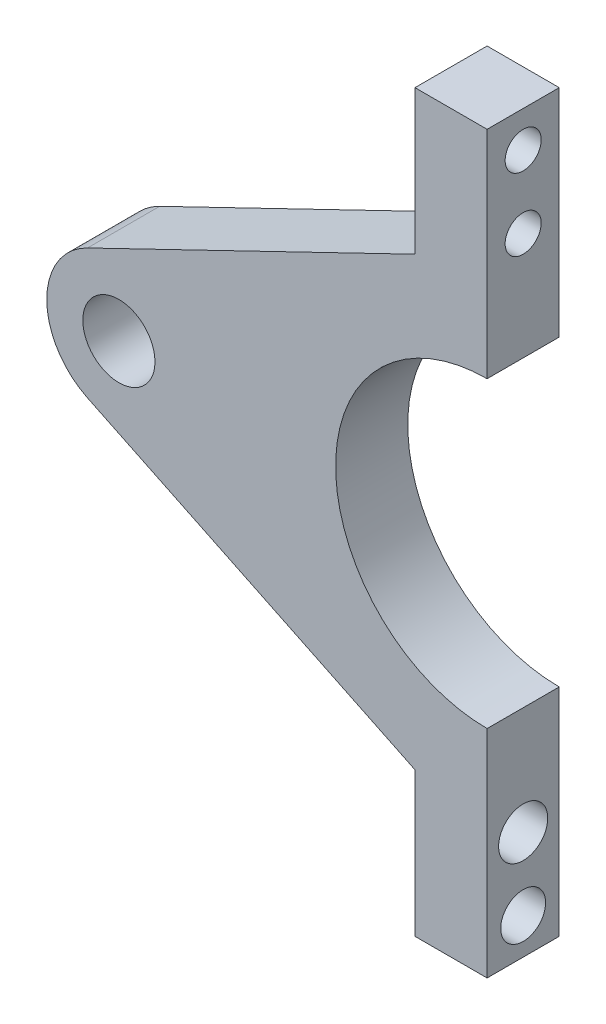
SolidWorks part; units mm, degrees
ref_plane "Front Plane" through (0, 0, 0) normal (0, 0, 1) x (1, 0, 0)
ref_plane "Top Plane" through (0, 0, 0) normal (0, 1, 0) x (1, 0, 0)
ref_plane "Right Plane" through (0, 0, 0) normal (1, 0, 0) x (0, 0, -1)
sketch "Sketch1" plane through (0, 0, 0) normal (0, 0, 1) x (1, 0, 0)
  line L0 (-122.0959, 24.2997) -> (-122.0959, 54.25)
  line L1 (-122.0959, 54.25) -> (-132.0959, 54.25)
  line L2 (-132.0959, 54.25) -> (-132.0959, 34.25)
  line L3 (-132.0959, 34.25) -> (-177.4962, 12.3029)
  line L4 (-24.0245, 3.2997) -> (-196.1204, 3.2997) construction
  line L5 (-122.0959, -17.7003) -> (-122.0959, -47.6506)
  line L6 (-122.0959, -47.6506) -> (-132.0959, -47.6506)
  line L7 (-132.0959, -47.6506) -> (-132.0959, -27.6506)
  line L8 (-132.0959, -27.6506) -> (-177.4962, -5.7035)
  arc A2 (-177.4962, 12.3029) -> (-177.4962, -5.7035) centre (-173.1439, 3.2997) ccw
  arc A3 (-122.0959, 24.2997) -> (-122.0959, -17.7003) centre (-122.0959, 3.2997) ccw
  point P2 (-183.1439, 3.2997)
  dimension "D2" = 101.9006
  dimension "D6" = 10
  dimension "D1" = 42
  dimension "D3" = 10
  dimension "D4" = 20
  dimension "D5" = 61.048
extrude "Boss-Extrude2" add sketch "Sketch1" against normal blind 10
sketch "Sketch2" plane through (0, 0, 0) normal (0, 0, 1) x (1, 0, 0)
  circle A0 centre (-173.1439, 3.2997) radius 5
  dimension "D1" = 10
extrude "Cut-Extrude1" cut sketch "Sketch2" against normal through all
sketch "Sketch3" plane through (-122.0959, 0, 0) normal (1, 0, 0) x (0, 0, -1)
  line L0 (10, 54.25) -> (0, 54.25) construction
  line L1 (10, -47.6506) -> (0, -47.6506) construction
  circle A0 centre (5, 49.25) radius 2.5
  circle A1 centre (5, 39.25) radius 2.5
  circle A2 centre (5, -42.6506) radius 3.1126
  circle A3 centre (5, -32.6506) radius 3.4066
  dimension "D3" = 5
  dimension "D4" = 5
  dimension "D5" = 5
  dimension "D1" = 5
  dimension "D2" = 10
  dimension "D6" = 10
extrude "Cut-Extrude2" cut sketch "Sketch3" against normal through all
